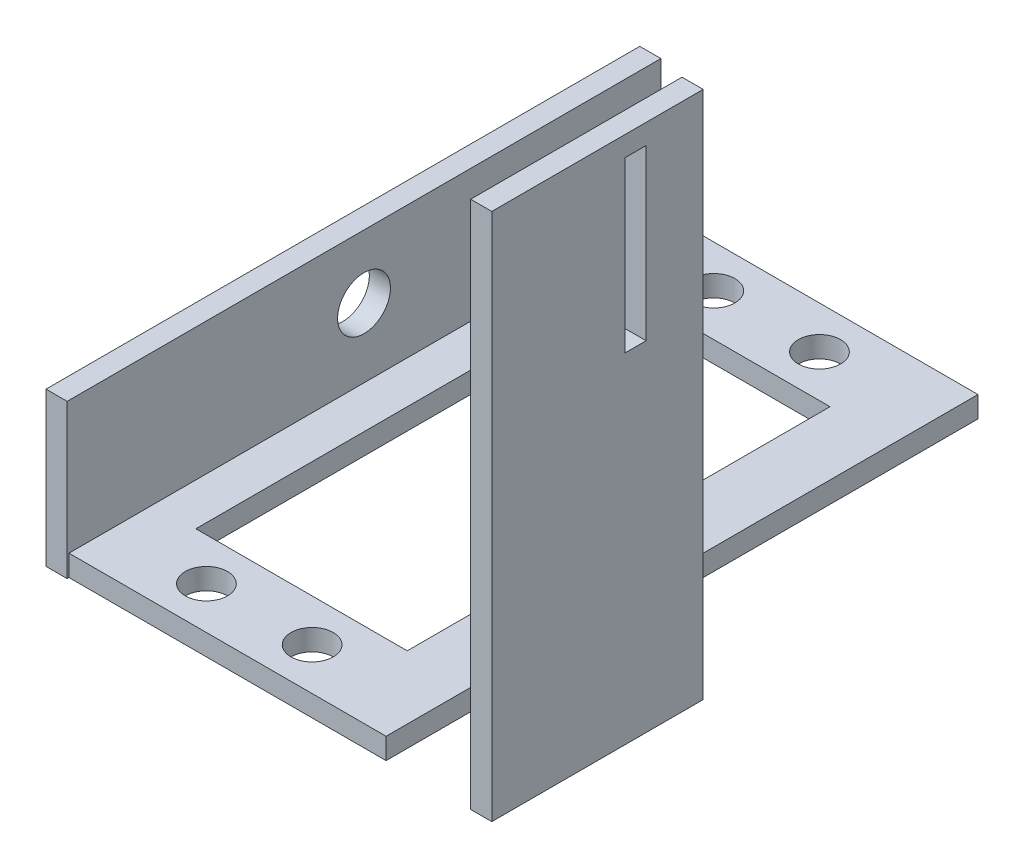
SolidWorks part; units mm, degrees
ref_plane "Front Plane" through (0, 0, 0) normal (0, 0, 1) x (1, 0, 0)
ref_plane "Top Plane" through (0, 0, 0) normal (0, 1, 0) x (1, 0, 0)
ref_plane "Right Plane" through (0, 0, 0) normal (1, 0, 0) x (0, 0, -1)
sketch "Sketch1" plane through (0, 0, 0) normal (0, 1, 0) x (1, 0, 0)
  line L1 (-10.3859, -11.5013) -> (9.6141, -11.5013)
  line L2 (-10.3859, -11.5013) -> (-10.3859, -19.5013)
  line L3 (-10.3859, -19.5013) -> (9.6141, -19.5013)
  line L4 (9.6141, -11.5013) -> (9.6141, -19.5013)
  line L5 (-10.3859, 36.4987) -> (9.6141, 36.4987)
  line L6 (-10.3859, 36.4987) -> (-10.3859, 28.4987)
  line L7 (-10.3859, 28.4987) -> (9.6141, 28.4987)
  line L8 (9.6141, 36.4987) -> (9.6141, 28.4987)
  circle A0 centre (4.6141, -15.5013) radius 2
  circle A1 centre (-5.3859, -15.5013) radius 2
  circle A2 centre (4.6141, 32.4987) radius 2
  circle A3 centre (-5.3859, 32.4987) radius 2
  dimension "D5" = 5
  dimension "D9" = 40
  dimension "D1" = 20
  dimension "D2" = 20
  dimension "D3" = 8
  dimension "D4" = 8
  dimension "D6" = 5
  dimension "D7" = 5
  dimension "D8" = 5
  dimension "D10" = 48
extrude "Boss-Extrude1" add sketch "Sketch1" along normal blind 2
sketch "Sketch6" plane through (9.6141, 0, 0) normal (1, 0, 0) x (0, 0, -1)
  line L1 (-19.5013, 2) -> (36.4987, 2)
  line L2 (-19.5013, 2) -> (-19.5013, 0)
  line L3 (-19.5013, 0) -> (36.4987, 0)
  line L4 (36.4987, 2) -> (36.4987, 0)
extrude "Boss-Extrude5" add sketch "Sketch6" along normal blind 6
sketch "Sketch10" plane through (-10.3859, 0, 0) normal (-1, 0, 0) x (0, 0, 1)
  line L1 (-36.4987, 2) -> (19.5013, 2)
  line L2 (-36.4987, 2) -> (-36.4987, 0)
  line L3 (-36.4987, 0) -> (19.5013, 0)
  line L4 (19.5013, 2) -> (19.5013, 0)
extrude "Boss-Extrude7" add sketch "Sketch10" along normal blind 4
sketch "Sketch11" plane through (-14.3859, 0, 0) normal (-1, 0, 0) x (0, 0, 1)
  line L1 (-36.4987, 0) -> (19.6765, 0)
  line L2 (-36.4987, 0) -> (-36.4987, 14.5283)
  line L3 (-36.4987, 14.5283) -> (19.6765, 14.5283)
  line L4 (19.6765, 0) -> (19.6765, 14.5283)
extrude "Boss-Extrude8" add sketch "Sketch11" along normal blind 2
sketch "Sketch12" plane through (-16.3859, 0, 0) normal (-1, 0, 0) x (0, 0, 1)
  line L0 (19.6765, 14.5283) -> (-36.4987, 14.5283) construction
  circle A0 centre (-8.4111, 8.5283) radius 2.5
  dimension "D1" = 6
extrude "Cut-Extrude3" cut sketch "Sketch12" against normal blind 2
sketch "Sketch13" plane through (15.6141, 0, 0) normal (1, 0, 0) x (0, 0, -1)
  line L0 (-19.5013, 2) -> (-19.5013, 0) construction
  line L1 (-11.5013, 42) -> (8.4987, 42)
  line L2 (-11.5013, 42) -> (-11.5013, -8)
  line L3 (-11.5013, -8) -> (8.4987, -8)
  line L4 (8.4987, 42) -> (8.4987, -8)
  line L5 (36.4987, 2) -> (-19.5013, 2) construction
  line L7 (1.1023, 24.103) -> (3.1023, 24.103)
  line L8 (1.1023, 24.103) -> (1.1023, 40.103)
  line L9 (1.1023, 40.103) -> (3.1023, 40.103)
  line L10 (3.1023, 24.103) -> (3.1023, 40.103)
  dimension "D1" = 50
  dimension "D2" = 20
  dimension "D3" = 8
  dimension "D4" = 40
  dimension "D5" = 2
  dimension "D6" = 16
extrude "Boss-Extrude9" add sketch "Sketch13" along normal blind 2
